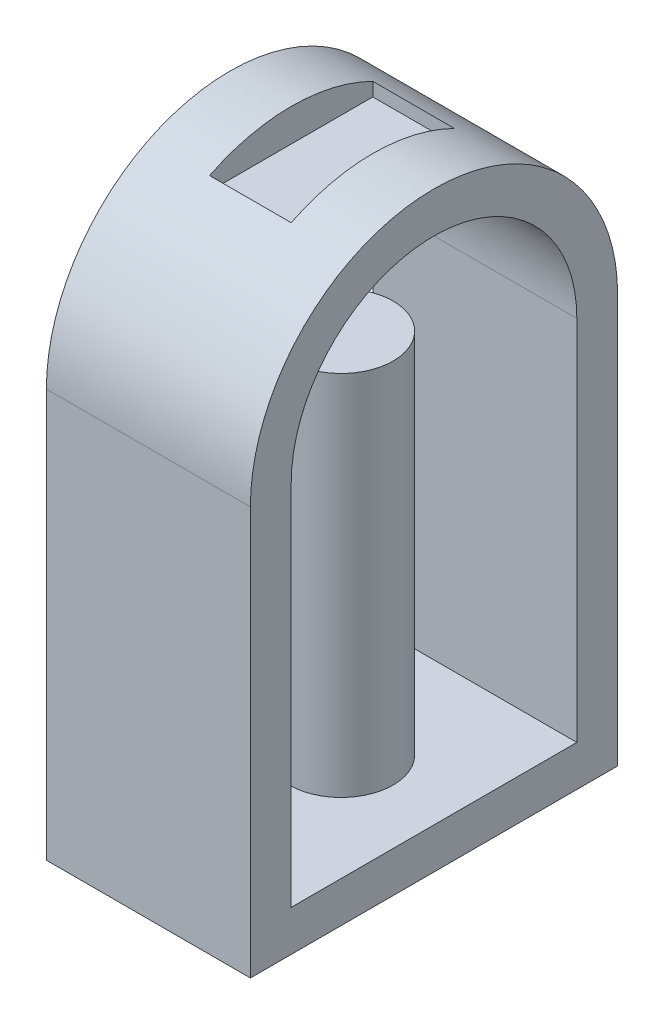
SolidWorks part; units mm, degrees
ref_plane "Front Plane" through (0, 0, 0) normal (0, 0, 1) x (1, 0, 0)
ref_plane "Top Plane" through (0, 0, 0) normal (0, 1, 0) x (1, 0, 0)
ref_plane "Right Plane" through (0, 0, 0) normal (1, 0, 0) x (0, 0, -1)
sketch "Sketch1" plane through (0, 0, 0) normal (1, 0, 0) x (0, 0, -1)
  line L0 (-25.4, -25.4) -> (-25.4, 228.6)
  line L1 (0, 0) -> (177.8, 0)
  line L2 (0, 0) -> (0, 228.6)
  line L3 (0, 228.6) -> (177.8, 228.6) construction
  line L4 (177.8, 0) -> (177.8, 228.6)
  line L5 (203.2, -25.4) -> (203.2, 228.6)
  line L6 (-25.4, -25.4) -> (203.2, -25.4)
  arc A0 (0, 228.6) -> (177.8, 228.6) centre (88.9, 228.6) cw
  arc A1 (-25.4, 228.6) -> (203.2, 228.6) centre (88.9, 228.6) cw
  dimension "D1" = 177.8
  dimension "D2" = 228.6
  dimension "D3" = 25.4
extrude "Boss-Extrude1" add sketch "Sketch1" along normal blind 127
ref_plane "Plane1" through (0, 342.9, 0) normal (0, 1, 0) x (1, 0, 0)
sketch "Sketch2" plane through (0, 342.9, 0) normal (0, 1, 0) x (1, 0, 0)
  line L0 (88.9, 88.9) -> (127, 88.9) construction
  line L1 (38.1, 38.1) -> (88.9, 38.1)
  line L2 (38.1, 38.1) -> (38.1, 139.7)
  line L3 (38.1, 139.7) -> (88.9, 139.7)
  line L4 (88.9, 38.1) -> (88.9, 139.7)
  line L5 (127, -25.4) -> (127, 203.2) construction
  line L6 (63.5, 139.7) -> (63.5, 203.2) construction
  line L7 (127, 203.2) -> (0, 203.2) construction
  dimension "D1" = 50.8
  dimension "D2" = 101.6
extrude "Cut-Extrude1" cut sketch "Sketch2" against normal blind 20.32
ref_plane "Plane2" through (0, 89.2098, -111.5122) normal (0, 0.6247, -0.7809) x (-1, 0, 0)
ref_plane "Plane3" through (0, 2.478, 3.0976) normal (0, -0.6247, -0.7809) x (-1, 0, 0)
ref_plane "Plane4" through (0, 228.6, 0) normal (0, 1, 0) x (1, 0, 0)
sketch "Sketch3" plane through (0, 228.6, 0) normal (0, 1, 0) x (1, 0, 0)
  circle A0 centre (60.4713, 97.6298) radius 32.3622
extrude "Boss-Extrude2" add sketch "Sketch3" against normal up to next
ref_plane "Plane5" through (0, 0, -330.2) normal (0, 0, -1) x (-1, 0, 0)
ref_plane "Plane6" through (0, 0, -88.9) normal (0, 0, -1) x (-1, 0, 0)
ref_plane "Plane7" through (0, 87.5494, -73.4627) normal (0, -0.766, 0.6428) x (-1, 0, 0)
ref_plane "Plane8" through (0, 330.9907, 0) normal (0, 1, 0) x (1, 0, 0)
